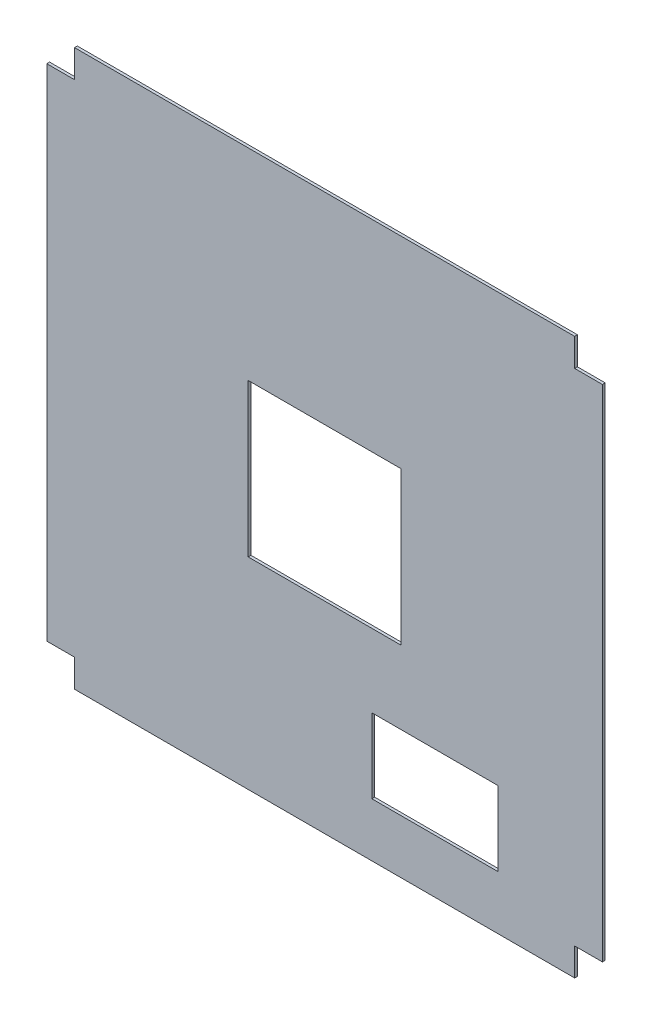
SolidWorks part; units mm, degrees
ref_plane "前视基准面" through (0, 0, 0) normal (0, 0, 1) x (1, 0, 0)
ref_plane "上视基准面" through (0, 0, 0) normal (0, 1, 0) x (1, 0, 0)
ref_plane "右视基准面" through (0, 0, 0) normal (1, 0, 0) x (0, 0, -1)
sketch "草图1" plane through (0, 0, 0) normal (0, 0, 1) x (1, 0, 0)
  line L0 (380, -10) -> (370, 0) construction
  line L1 (10, 380) -> (370, 380)
  line L2 (-10, 360) -> (-10, 0)
  line L3 (10, -20) -> (370, -20)
  line L4 (390, 360) -> (390, 0)
  line L5 (0, 370) -> (380, -10) construction
  line L6 (0, -10) -> (380, 370) construction
  line L9 (390, 360) -> (370, 360)
  line L10 (370, 380) -> (370, 360)
  line L11 (380, 370) -> (370, 360) construction
  line L12 (390, 360) -> (370, 380) construction
  line L13 (370, -20) -> (390, 0) construction
  line L16 (390, 0) -> (370, 0)
  line L17 (370, -20) -> (370, 0)
  line L18 (0, -10) -> (10, 0) construction
  line L19 (-10, 0) -> (10, -20) construction
  line L22 (10, -20) -> (10, 0)
  line L23 (-10, 0) -> (10, 0)
  line L24 (0, 370) -> (10, 360) construction
  line L25 (10, 380) -> (-10, 360) construction
  line L28 (-10, 360) -> (10, 360)
  line L29 (10, 380) -> (10, 360)
  point P0 (190, 180)
  point P5 (380, 370)
  point P17 (380, -10)
  point P22 (0, -10)
  point P27 (0, 370)
  point P32 (190, 180)
  dimension "D1" = 4
extrude "凸台-拉伸1" add sketch "草图1" along normal blind 2
sketch "草图2" plane through (0, 0, 2) normal (0, 0, 1) x (1, 0, 0)
  line L1 (135, 125) -> (245, 125)
  line L6 (135, 125) -> (135, 235)
  line L7 (135, 235) -> (245, 235)
  line L8 (245, 125) -> (245, 235)
  line L9 (135, 125) -> (245, 235) construction
  line L10 (135, 235) -> (245, 125) construction
  point P0 (190, 180)
  point P3 (190, 260)
  dimension "D1" = 110
extrude "切除-拉伸1" cut sketch "草图2" against normal blind 2
sketch "草图3" plane through (0, 0, 2) normal (0, 0, 1) x (1, 0, 0)
  line L0 (190, 180) -> (190, 80.8634) construction
  line L6 (224.0259, 18.7375) -> (314.7618, 18.7375)
  line L7 (224.0259, 18.7375) -> (224.0259, 72.3541)
  line L8 (224.0259, 72.3541) -> (314.7618, 72.3541)
  line L9 (314.7618, 18.7375) -> (314.7618, 72.3541)
  line L10 (224.0259, 18.7375) -> (314.7618, 72.3541) construction
  line L11 (224.0259, 72.3541) -> (314.7618, 18.7375) construction
  point P2 (269.3939, 45.5458)
extrude "切除-拉伸2" cut sketch "草图3" against normal blind 75
sketch "草图5" plane through (0, 0, 2) normal (0, 0, 1) x (1, 0, 0)
  line L0 (134, 260.3952) -> (670, 260.3952) construction
